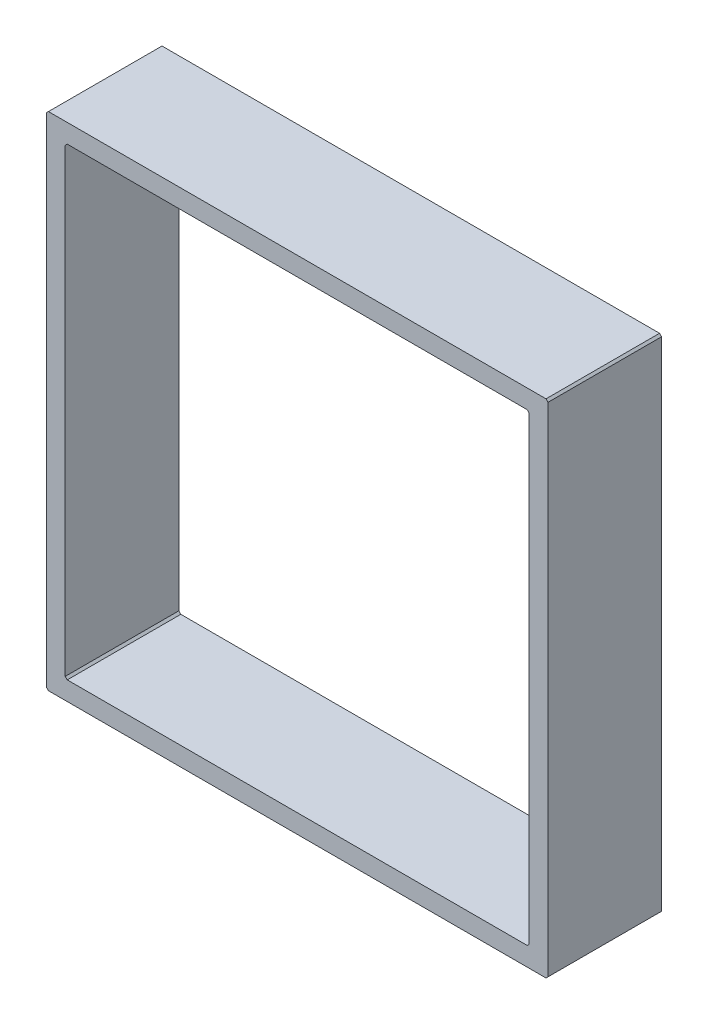
SolidWorks part; units mm, degrees
material "6061 Alloy"
ref_plane "Front" through (0, 0, 0) normal (0, 0, 1) x (1, 0, 0)
ref_plane "Top" through (0, 0, 0) normal (0, 1, 0) x (1, 0, 0)
ref_plane "Right" through (0, 0, 0) normal (1, 0, 0) x (0, 0, -1)
sketch "Sketch2" plane through (0, 0, 0) normal (0, 0, 1) x (1, 0, 0)
  line L6 (0, 0) -> (-61.1188, 0) construction
  line L7 (0, 0) -> (0, 61.1188) construction
  line L8 (0, 61.1188) -> (-61.1188, 61.1187)
  line L9 (-61.1188, 61.1187) -> (-61.1188, 0)
  dimension "D1" = 61.1187
extrude "Extrude-Thin1" add sketch "Sketch2" along normal mid plane 28.75 separate body thin thin type mid plane wall 4.7625
chamfer "Chamfer1" distance 0.508 angle 45 2 edges at (-63.5, 63.5, 0) (-58.7375, 58.7375, 0)
mirror "Mirror1" about plane through (0, 63.5, 14.375) normal (1, 0, 0) of bodies 103
mirror "Mirror2" about plane through (-58.7375, 0, 14.375) normal (0, -1, 0) of bodies 104
